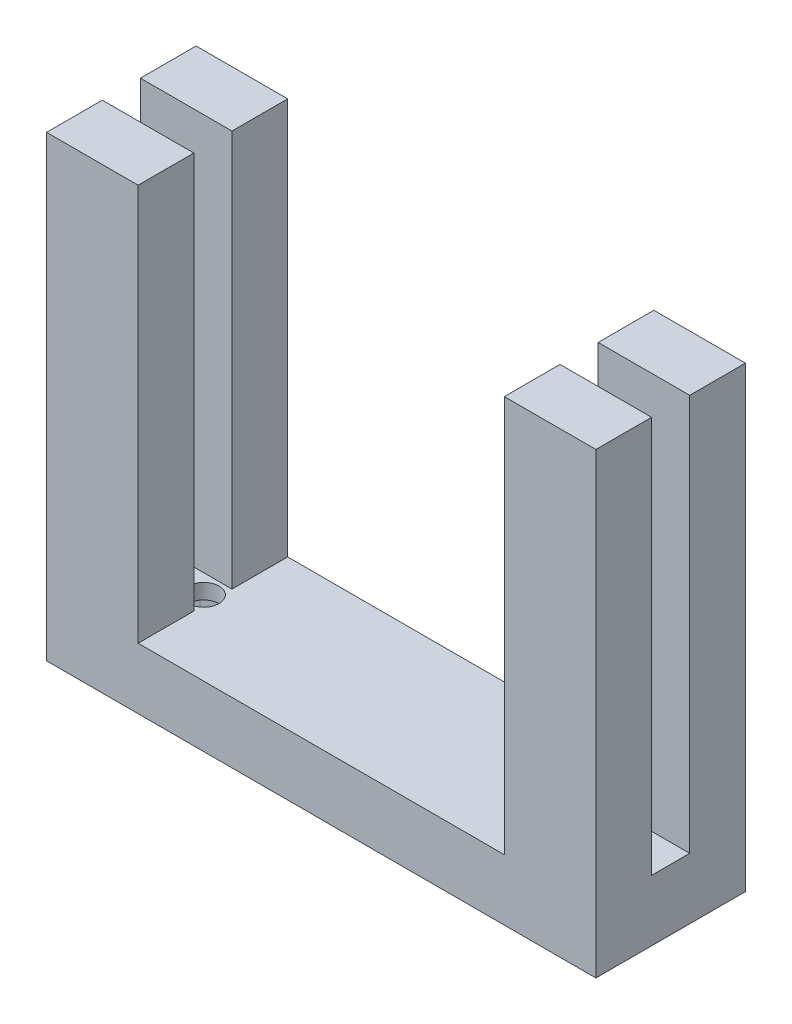
SolidWorks part; units mm, degrees
ref_plane "前视基准面" through (0, 0, 0) normal (0, 0, 1) x (1, 0, 0)
ref_plane "上视基准面" through (0, 0, 0) normal (0, 1, 0) x (1, 0, 0)
ref_plane "右视基准面" through (0, 0, 0) normal (1, 0, 0) x (0, 0, -1)
sketch "草图1" plane through (0, 0, 0) normal (0, 1, 0) x (1, 0, 0)
  line L1 (-18, 4.9) -> (18, 4.9)
  line L2 (-18, 4.9) -> (-18, -4.9)
  line L3 (-18, -4.9) -> (18, -4.9)
  line L4 (18, 4.9) -> (18, -4.9)
  line L5 (-18, 4.9) -> (18, -4.9) construction
  line L6 (-18, -4.9) -> (18, 4.9) construction
  point P0 (0, 0)
  dimension "D1" = 9.8
  dimension "D2" = 36
extrude "凸台-拉伸1" add sketch "草图1" along normal blind 30
sketch "草图2" plane through (18, 0, 0) normal (1, 0, 0) x (0, 0, -1)
  line L0 (0, 30) -> (0, 0) construction
  line L1 (-4.9, 30) -> (4.9, 30) construction
  line L2 (-4.9, 0) -> (4.9, 0) construction
  line L3 (-4.9, 4) -> (4.9, 4) construction
  line L4 (-4.9, 30) -> (-4.9, 0) construction
  line L5 (4.9, 30) -> (4.9, 0) construction
  line L6 (-1.25, 30) -> (-1.25, 4)
  line L7 (1.25, 30) -> (1.25, 4)
  line L8 (-1.25, 30) -> (1.25, 30)
  line L9 (-1.25, 4) -> (1.25, 4)
  dimension "D1" = 4
  dimension "D2" = 1.25
extrude "切除-拉伸1" cut sketch "草图2" against normal through all
sketch "草图3" plane through (0, 0, -4.9) normal (0, 0, -1) x (-1, 0, 0)
  line L0 (0, 14.8276) -> (0, 0) construction
  line L1 (-18, 0) -> (18, 0) construction
  line L2 (-18, 4) -> (18, 4) construction
  line L3 (-18, 30) -> (-18, 0) construction
  line L4 (18, 30) -> (18, 0) construction
  line L5 (-12, 30) -> (-12, 4)
  line L6 (-18, 30) -> (18, 30) construction
  line L7 (12, 30) -> (12, 4)
  line L8 (-12, 4) -> (12, 4)
  line L9 (-12, 30) -> (12, 30)
  dimension "D1" = 4
  dimension "D2" = 12
extrude "切除-拉伸2" cut sketch "草图3" against normal through all
sketch "草图5" plane through (0, 0, 0) normal (0, -1, 0) x (1, 0, 0)
  line L0 (0, -4.9) -> (0, 4.9) construction
  line L1 (18, -4.9) -> (-18, -4.9) construction
  line L2 (-18, 4.9) -> (18, 4.9) construction
  line L3 (18, 0) -> (-18, 0) construction
  line L4 (18, 4.9) -> (18, -4.9) construction
  line L5 (-18, -4.9) -> (-18, 4.9) construction
  line L6 (14.75, -4.9) -> (14.75, 5.1593) construction
  line L7 (-14.75, -4.9) -> (-14.75, 5.1593) construction
  line L8 (14.9661, 2.114) -> (0.3686, 3.6062)
  line L9 (-0.3686, 3.6062) -> (-14.9661, 2.114)
  line L10 (-14.9661, -2.114) -> (-0.3686, -3.6062)
  line L11 (14.9661, -2.114) -> (0.3686, -3.6062)
  arc A0 (14.9661, -2.114) -> (14.9661, 2.114) centre (14.75, 0) ccw
  arc A1 (0.3686, 3.6062) -> (-0.3686, 3.6062) centre (0, 0) ccw
  arc A2 (-14.9661, -2.114) -> (-14.9661, 2.114) centre (-14.75, 0) cw
  arc A3 (-0.3686, -3.6062) -> (0.3686, -3.6062) centre (0, 0) ccw
  dimension "D2" = 4.25
  dimension "D3" = 7.25
  dimension "D1" = 14.75
extrude "切除-拉伸3" cut sketch "草图5" against normal blind 3
sketch "草图9" plane through (0, 3, 0) normal (0, -1, 0) x (1, 0, 0)
  line L0 (0, -3.625) -> (0, 3.625) construction
  line L1 (16.875, 0) -> (-16.875, 0) construction
  line L2 (12.6, -2.06) -> (12.6, 1.9737) construction
  arc A0 (-0.3686, -3.6062) -> (0.3686, -3.6062) centre (0, 0) ccw construction
  arc A1 (0.3686, 3.6062) -> (-0.3686, 3.6062) centre (0, 0) ccw construction
  arc A2 (14.9661, -2.114) -> (14.9661, 2.114) centre (14.75, 0) ccw construction
  arc A3 (-14.9661, 2.114) -> (-14.9661, -2.114) centre (-14.75, 0) ccw construction
  circle A4 centre (12.6, 0) radius 1
  circle A5 centre (-12.6, 0) radius 1
  dimension "D2" = 2
  dimension "D1" = 12.6
extrude "切除-拉伸4" cut sketch "草图9" against normal up to next
